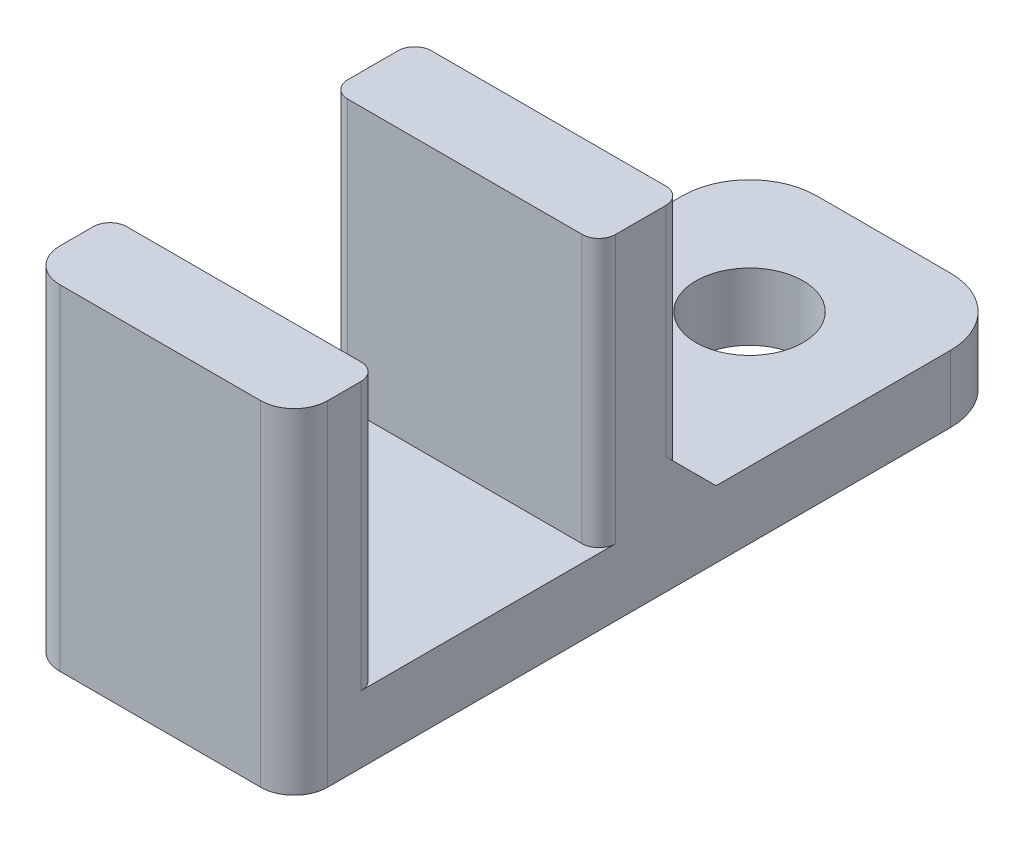
SolidWorks part; units mm, degrees
ref_plane "Plano frontal" through (0, 0, 0) normal (0, 0, 1) x (1, 0, 0)
ref_plane "Plano superior" through (0, 0, 0) normal (0, 1, 0) x (1, 0, 0)
ref_plane "Plano direito" through (0, 0, 0) normal (1, 0, 0) x (0, 0, -1)
sketch "Esboço1" plane through (0, 0, 0) normal (0, 1, 0) x (1, 0, 0)
  line L1 (-4, -10.8) -> (4, -10.8)
  line L2 (-4, -10.8) -> (-4, 10.8)
  line L3 (-4, 10.8) -> (4, 10.8)
  line L4 (4, -10.8) -> (4, 10.8)
  line L5 (-4, -10.8) -> (4, 10.8) construction
  line L6 (-4, 10.8) -> (4, -10.8) construction
  point P0 (0, 0)
  dimension "D1" = 8
  dimension "D2" = 21.6
extrude "Ressalto-extrusão1" add sketch "Esboço1" along normal blind 2
sketch "Esboço2" plane through (0, 2, 0) normal (0, 1, 0) x (1, 0, 0)
  line L0 (4, -10.8) -> (4, 10.8) construction
  line L1 (-4, -10.8) -> (4, -10.8)
  line L2 (-4, -10.8) -> (-4, -8.3)
  line L3 (-4, -8.3) -> (4, -8.3)
  line L4 (4, -10.8) -> (4, -8.3)
  line L5 (-4, 10.8) -> (-4, -10.8) construction
  line L6 (-4, -1.7) -> (4, -1.7)
  line L7 (-4, -1.7) -> (-4, 0.8)
  line L8 (-4, 0.8) -> (4, 0.8)
  line L9 (4, -1.7) -> (4, 0.8)
  dimension "D1" = 2.5
  dimension "D2" = 2.5
  dimension "D3" = 6.6
extrude "Ressalto-extrusão2" add sketch "Esboço2" along normal blind 8
sketch "Esboço3" plane through (0, 2, 0) normal (0, 1, 0) x (1, 0, 0)
  line L0 (4, 0.8) -> (4, 10.8) construction
  line L1 (4, 10.8) -> (-4, 10.8) construction
  circle A0 centre (0, 6.8) radius 1.6
  dimension "D1" = 3.2
  dimension "D2" = 4
  dimension "D3" = 4
extrude "Corte-extrusão1" cut sketch "Esboço3" against normal blind 8
fillet "Filete1" radius 2 1 edges at (-4, 1, -10.8)
fillet "Filete2" radius 2 1 edges at (4, 1, -10.8)
fillet "Filete3" radius 1 1 edges at (4, 5, 10.8)
fillet "Filete4" radius 1 1 edges at (-4, 5, 10.8)
chamfer "Chanfro1" distance 1 angle 45 1 edges at (0, 2, -0.8)
fillet "Filete5" radius 0.5 1 edges at (4, 6.5, -0.8)
fillet "Filete6" radius 0.5 1 edges at (-4, 6.5, -0.8)
fillet "Filete7" radius 0.5 1 edges at (4, 6, 8.3)
fillet "Filete8" radius 0.5 1 edges at (-4, 6, 8.3)
fillet "Filete9" radius 0.5 1 edges at (-4, 6, 1.7)
fillet "Filete10" radius 0.5 1 edges at (4, 6, 1.7)
